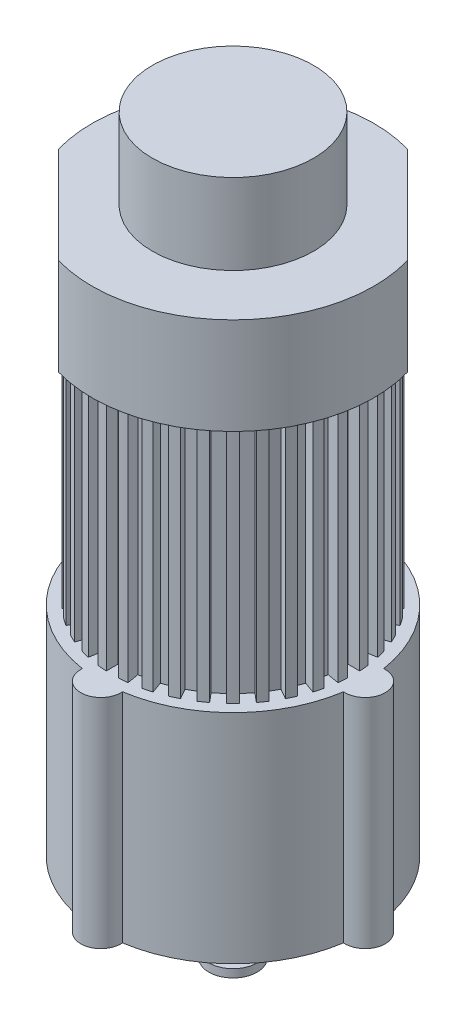
SolidWorks part; units mm, degrees
ref_plane "前视基准面" through (0, 0, 0) normal (0, 0, 1) x (1, 0, 0)
ref_plane "上视基准面" through (0, 0, 0) normal (0, 1, 0) x (1, 0, 0)
ref_plane "右视基准面" through (0, 0, 0) normal (1, 0, 0) x (0, 0, -1)
sketch "草图1" plane through (0, 0, 0) normal (0, 1, 0) x (1, 0, 0)
  circle A0 centre (0, 0) radius 8.2
  dimension "D1" = 16.4
extrude "凸台-拉伸1" add sketch "草图1" along normal blind 1
sketch "草图2" plane through (0, 1, 0) normal (0, 1, 0) x (1, 0, 0)
  line L0 (0, 12.8701) -> (0, -12.5799) construction
  line L1 (0, 0) -> (17.876, 0) construction
  circle A0 centre (0, 0) radius 16.4
  circle A1 centre (16.4, 0) radius 2.5
  circle A2 centre (0, 16.4) radius 2.5
  circle A6 centre (0, -16.4) radius 2.5
  circle A7 centre (-16.4, 0) radius 2.5
  point P17 (0, 0)
  point P19 (3.1472, -3.1472)
  dimension "D1" = 32.8
  dimension "D2" = 5
  dimension "D3" = 4
extrude "凸台-拉伸2" add sketch "草图2" along normal blind 27
sketch "草图3" plane through (0, 28, 0) normal (0, 1, 0) x (1, 0, 0)
  circle A0 centre (0, 0) radius 15
  dimension "D1" = 30
extrude "凸台-拉伸4" add sketch "草图3" along normal offset from surface (43 mm away) 70 up to face at (0, 1, 8.2)
sketch "草图4" plane through (0, 71, 0) normal (0, 1, 0) x (1, 0, 0)
  circle A0 centre (0, 0) radius 10
  dimension "D1" = 20
extrude "凸台-拉伸5" add sketch "草图4" along normal blind 10
sketch "草图5" plane through (0, 71, 0) normal (0, 1, 0) x (1, 0, 0)
  line L0 (-17.5, 0) -> (17.5, 0) construction
  line L6 (-16.8271, -4.8062) -> (-4.8062, -16.8271)
  line L7 (-12.3744, 12.3744) -> (12.3744, -12.3744) construction
  line L8 (4.8062, 16.8271) -> (16.8271, 4.8062)
  arc A8 (-4.8062, -16.8271) -> (16.8271, 4.8062) centre (0, 0) ccw
  arc A9 (-16.8271, -4.8062) -> (-4.8062, -16.8271) centre (0, 0) ccw construction
  arc A10 (16.8271, 4.8062) -> (4.8062, 16.8271) centre (0, 0) ccw construction
  arc A11 (-4.8062, 16.8271) -> (-16.8271, -4.8062) centre (0, 0) ccw
  arc A12 (4.8062, 16.8271) -> (-4.8062, 16.8271) centre (0, 0) ccw
  point P1 (5.2209, 16.7031)
  point P4 (0, 0)
  point P8 (-3.9485, 17.0487)
  point P9 (-3.2178, 17.2261)
  point P14 (0, 0)
  dimension "D2" = 45
  dimension "D1" = 35
  dimension "D3" = 17
extrude "凸台-拉伸6" add sketch "草图5" against normal blind 12
sketch "草图6" plane through (0, 28, 0) normal (0, 1, 0) x (1, 0, 0)
  line L0 (0, 0) -> (-18.4515, 0) construction
  line L2 (-16.5, -0.75) -> (-13.5, -0.75)
  line L3 (-16.5, -0.75) -> (-16.5, 0.75)
  line L4 (-16.5, 0.75) -> (-13.5, 0.75)
  line L5 (-13.5, -0.75) -> (-13.5, 0.75)
  line L6 (-16.5, -0.75) -> (-13.5, 0.75) construction
  line L7 (-16.5, 0.75) -> (-13.5, -0.75) construction
  circle A0 centre (0, 0) radius 15 construction
  circle A1 centre (0, 0) radius 15
  point P3 (-15, 0)
  circle M4 centre (0, 0) radius 15
  dimension "D1" = 1.5
  dimension "D2" = 3
extrude "切除-拉伸1" cut sketch "草图6" along normal up to surface (31 mm away) contours L4 L3 L2 M4 | L2 L5 L4 M4
pattern_circular "阵列(圆周)1" count 36 every 10 about axis through (0, 0, 0) along (0, 1, 0) of "切除-拉伸1"
sketch "草图7" plane through (0, 0, 0) normal (0, -1, 0) x (1, 0, 0)
  circle A1 centre (0, 0) radius 3
  dimension "D1" = 6
extrude "凸台-拉伸7" add sketch "草图7" along normal blind 10
ref_plane "基准面1" through (0, -9, 0) normal (0, -1, 0) x (-1, 0, 0)
sketch "草图9" plane through (0, -9, 0) normal (0, -1, 0) x (-1, 0, 0)
  line L1 (3, 0) -> (0, -3)
  line L2 (0, -3) -> (-3, 0)
  circle A1 centre (0, 0) radius 3
  arc A2 (-3, 0) -> (3, 0) centre (0, 0) ccw
  dimension "D1" = 0
extrude "切除-拉伸2" cut sketch "草图9" against normal blind 5 contours L2 A2 | L1 A2
sketch "草图10" plane through (0, 1, 0) normal (0, -1, 0) x (1, 0, 0)
  circle A0 centre (0, 0) radius 12 construction
  arc A1 (-2.4927, -16.2095) -> (2.4927, -16.2095) centre (0, -16.4) ccw construction
  arc A3 (-2.4927, -16.2095) -> (2.4927, -16.2095) centre (0, -16.4) ccw construction
  circle A5 centre (-8.4853, -8.4853) radius 1.5
  circle A6 centre (-3.1058, 11.5911) radius 1.5
  circle A7 centre (11.5911, -3.1058) radius 1.5
  point P19 (0, 0)
  dimension "D1" = 20.0764
  dimension "D3" = 3
  dimension "D4" = 24
  dimension "D2" = 3
extrude "切除-拉伸3" cut sketch "草图10" against normal blind 15
